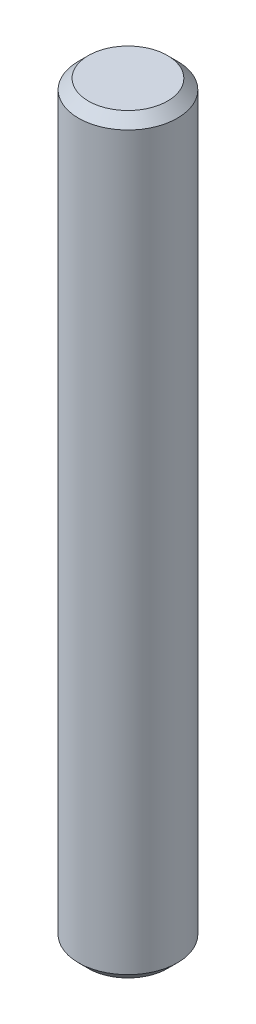
SolidWorks part; units mm, degrees
ref_plane "Front Plane" through (0, 0, 0) normal (0, 0, 1) x (1, 0, 0)
ref_plane "Top Plane" through (0, 0, 0) normal (0, 1, 0) x (1, 0, 0)
ref_plane "Right Plane" through (0, 0, 0) normal (1, 0, 0) x (0, 0, -1)
sketch "Sketch1" plane through (0, 0, 0) normal (0, 1, 0) x (1, 0, 0)
  circle A0 centre (0, 0) radius 5
  dimension "D1" = 10
extrude "Boss-Extrude1" add sketch "Sketch1" along normal mid plane 76
chamfer "Chamfer1" distance 1 angle 45 2 edges at (0, -38, 5) (0, 38, 5)
